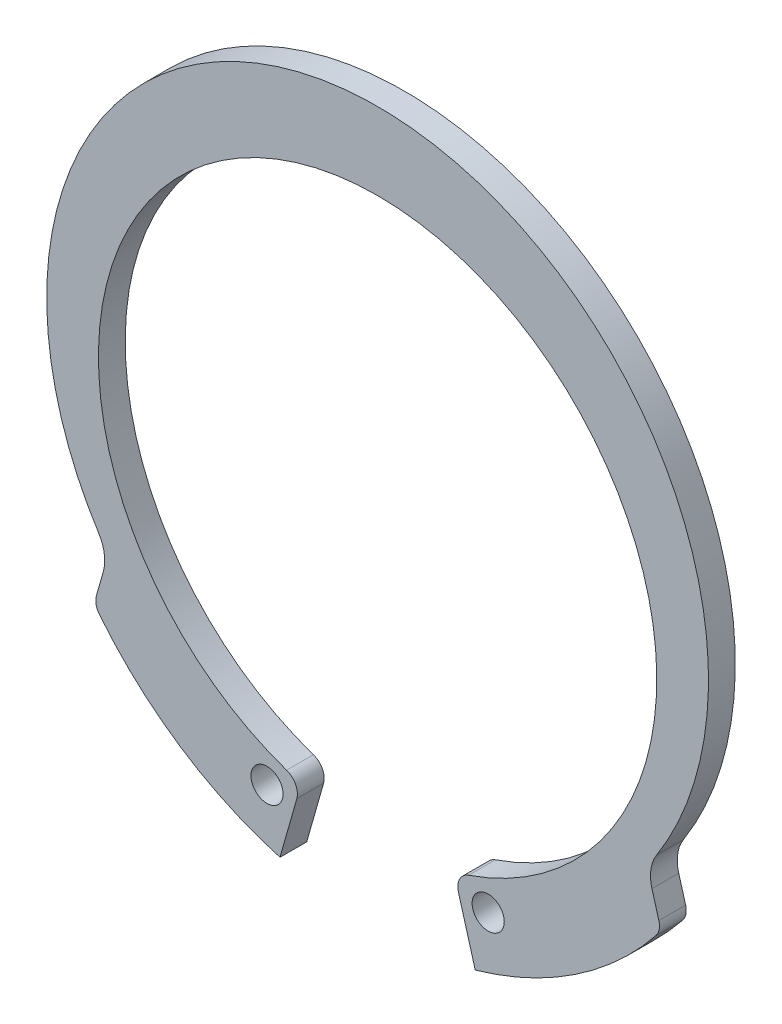
SolidWorks part; units mm, degrees
ref_plane "Plane1" through (0, 0, 0) normal (0, 0, 1) x (1, 0, 0)
ref_plane "Plane2" through (0, 0, 0) normal (0, 1, 0) x (1, 0, 0)
ref_plane "Plane3" through (0, 0, 0) normal (1, 0, 0) x (0, 0, -1)
sketch "Clipboard" plane through (0, 0, 0) normal (0, 0, 1) x (1, 0, 0)
  line L0 (0, 0) -> (1.7272, 0)
  line L1 (0, 0) -> (0, 0.9144)
  line L2 (0, 0) -> (0, -1.8288)
  circle A0 centre (0, 0) radius 0.381
  circle A1 centre (0, 0) radius 7.9375
  dimension "HoleDia" = 0.762
  dimension "BoreDia" = 15.875
  dimension "SmallSection" = 0.9144
  dimension "LugSection" = 1.8288
sketch "BodySke" plane through (0, 0, 0) normal (0, 0, 1) x (1, 0, 0)
  line L0 (0, 0) -> (0, 11.176) construction
  line L1 (0, 0) -> (10.8692, 0) construction
  line L2 (0, 0) -> (-7.3796, -4.1071) construction
  line L3 (0, 0) -> (7.3796, -4.1071) construction
  line L4 (-1.9145, -6.7199) -> (-2.314, -8.1223)
  line L5 (1.9145, -6.7199) -> (2.314, -8.1223)
  line L6 (6.502, -4.3571) -> (6.6655, -4.9312)
  line L7 (-6.502, -4.3571) -> (-6.6655, -4.9312)
  line L8 (-2.439, -6.1508) -> (-2.9421, -7.9165) construction
  line L9 (2.439, -6.1508) -> (2.9421, -7.9165) construction
  arc A0 (2.314, -8.1223) -> (6.5967, -5.2735) centre (0, 0) ccw
  arc A1 (-6.3587, -3.5389) -> (6.3587, -3.5389) centre (0, 0) ccw construction
  arc A2 (2.1567, -6.2553) -> (-2.1567, -6.2553) centre (0, 0) ccw
  arc A3 (-6.502, -4.3571) -> (-6.6104, -3.6161) centre (-7.3796, -4.1071) ccw
  arc A4 (6.6104, -3.6161) -> (6.502, -4.3571) centre (7.3796, -4.1071) ccw
  arc A5 (-6.5967, -5.2735) -> (-2.314, -8.1223) centre (0, 0) ccw
  arc A6 (6.5806, -3.6624) -> (-6.5806, -3.6624) centre (0, 0.6033) ccw construction
  arc A7 (6.6104, -3.6161) -> (-6.6104, -3.6161) centre (0, 0.6033) ccw
  circle A8 centre (0, 0) radius 8.4455 construction
  circle A9 centre (2.6208, -6.7888) radius 0.381
  circle A10 centre (-2.6208, -6.7888) radius 0.381
  arc A11 (-6.5967, -5.2735) -> (-6.6655, -4.9312) centre (-6.2991, -5.0356) cw
  arc A12 (-1.9145, -6.7199) -> (-2.1567, -6.2553) centre (-2.2809, -6.6155) ccw
  arc A13 (1.9145, -6.7199) -> (2.1567, -6.2553) centre (2.2809, -6.6155) cw
  arc A14 (6.5967, -5.2735) -> (6.6655, -4.9312) centre (6.2991, -5.0356) ccw
  dimension "GrooveDia" = 16.891
  dimension "InsideDia" = 13.2334
  dimension "HoleOffsetRad" = 7.2771
  dimension "HoleDia" = 0.762
  dimension "GapAngle" = 31.805
  dimension "LugAngle" = 121.805
  dimension "SmallRad" = 7.5311
  dimension "HoleOffset" = 0.6604
extrude "Body" add sketch "BodySke" against normal blind 0.635
equation "' \"BoreDia@Clipboard\" = 0.625"
equation "' \"Thickness@Body\" = 0.025"
equation "' \"GrooveDia@BodySke\" = 0.665"
equation "' \"LugSection@Clipboard\" = 0.072"
equation "' \"SmallSection@Clipboard\" = 0.036"
equation "' \"HoleDia@Clipboard\" = 0.03"
equation "' \"BoreDia@Clipboard\" = 0.75"
equation "' \"Thickness@Body\" = 0.035"
equation "' \"GrooveDia@BodySke\" = 0.796"
equation "' \"LugSection@Clipboard\" = 0.085"
equation "' \"SmallSection@Clipboard\" = 0.042"
equation "' \"HoleDia@Clipboard\" = 0.042"
equation "\"InsideDia@BodySke\" = \"GrooveDia@BodySke\" -  \"LugSection@Clipboard\" * 2"
equation "\"GapAngle@BodySke\" = 360 - 360 * 0.97 * ( \"BoreDia@Clipboard\" / \"GrooveDia@BodySke\" )"
equation "\"LugAngle@BodySke\" = \"GapAngle@BodySke\" + 90"
equation "\"SmallRad@BodySke\" =  \"InsideDia@BodySke\" / 2 +  \"SmallSection@Clipboard\""
equation "\"HoleOffsetRad@BodySke\" = (  \"BoreDia@Clipboard\" + \"InsideDia@BodySke\" ) / 4"
equation "\"HoleOffset@BodySke\" = \"HoleOffsetRad@BodySke\" - \"InsideDia@BodySke\" / 2"
equation "\"HoleDia@BodySke\" =  \"HoleDia@Clipboard\""
